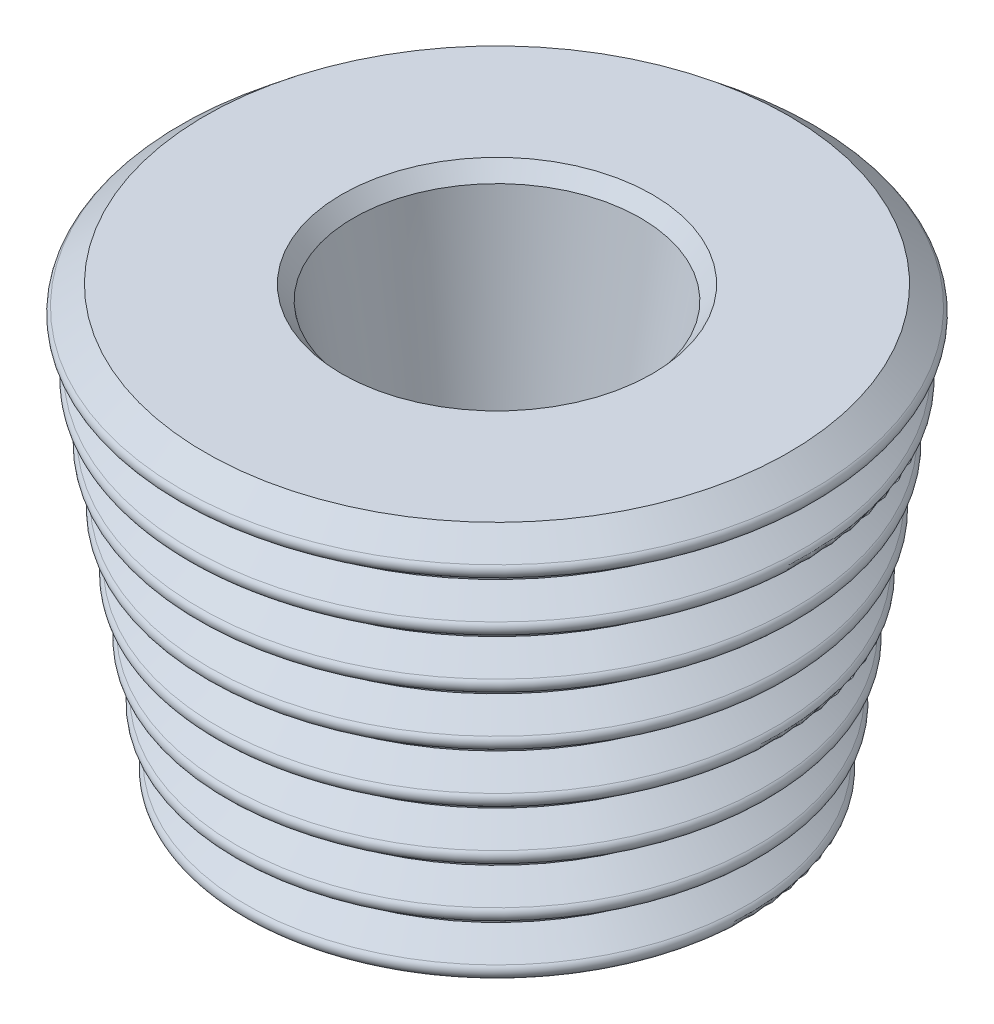
SolidWorks part; units mm, degrees
ref_plane "Plan de face" through (0, 0, 0) normal (0, 0, 1) x (1, 0, 0)
ref_plane "Plan de dessus" through (0, 0, 0) normal (0, 1, 0) x (1, 0, 0)
ref_plane "Plan de droite" through (0, 0, 0) normal (1, 0, 0) x (0, 0, -1)
sketch "Esquisse1" plane through (0, 0, 0) normal (0, 0, 1) x (1, 0, 0)
  line L0 (0, 0) -> (0, 20) construction
  line L1 (2.5, 0) -> (7.5, 0)
  line L2 (7.5, 0) -> (10, 15)
  line L3 (2.5, 0) -> (5, 15)
  line L4 (5, 15) -> (10, 15)
  line L5 (10, 15) -> (10.8238, 14.3219)
  line L6 (10.7526, 13.8947) -> (9.7534, 13.5204)
  line L7 (10.432, 11.9713) -> (9.4328, 11.5969)
  line L8 (9.6794, 13.0765) -> (10.5032, 12.3984)
  line L9 (10.1114, 10.0478) -> (9.1122, 9.6735)
  line L10 (9.3588, 11.1531) -> (10.1826, 10.4749)
  line L11 (9.7908, 8.1243) -> (8.7917, 7.75)
  line L12 (9.0383, 9.2296) -> (9.862, 8.5514)
  line L13 (9.4703, 6.2009) -> (8.4711, 5.8265)
  line L14 (8.7177, 7.3061) -> (9.5414, 6.628)
  line L15 (9.1497, 4.2774) -> (8.1505, 3.9031)
  line L16 (8.3971, 5.3827) -> (9.2209, 4.7045)
  line L17 (8.8291, 2.3539) -> (7.8299, 1.9796)
  line L18 (8.0765, 3.4592) -> (8.9003, 2.781)
  line L19 (8.5085, 0.4305) -> (7.5094, 0.0561)
  line L20 (7.756, 1.5357) -> (8.5797, 0.8576)
  arc A0 (9.4703, 6.2009) -> (9.5414, 6.628) centre (9.3826, 6.435) ccw
  arc A1 (9.1497, 4.2774) -> (9.2209, 4.7045) centre (9.062, 4.5115) ccw
  arc A2 (8.8291, 2.3539) -> (8.9003, 2.781) centre (8.7414, 2.588) ccw
  arc A3 (8.5085, 0.4305) -> (8.5797, 0.8576) centre (8.4208, 0.6646) ccw
  arc A4 (9.7908, 8.1243) -> (9.862, 8.5514) centre (9.7031, 8.3584) ccw
  arc A5 (10.1114, 10.0478) -> (10.1826, 10.4749) centre (10.0237, 10.2819) ccw
  arc A6 (10.432, 11.9713) -> (10.5032, 12.3984) centre (10.3443, 12.2054) ccw
  arc A7 (10.8238, 14.3219) -> (10.7526, 13.8947) centre (10.6649, 14.1288) cw
  point P46 (11.1581, 14.0466)
  dimension "D9" = 0.25
  dimension "D1" = 20
  dimension "D2" = 2.5
  dimension "D3" = 5
  dimension "D4" = 15
  dimension "D5" = 60
  dimension "D6" = 5
  dimension "D7" = 1.5
  dimension "D8" = 8
revolve "Révolution1" add sketch "Esquisse1" angle 360 about L0
chamfer "Chanfrein1" distance 0.5 angle 30 1 edges at (0, 15, -5)
chamfer "Chanfrein2" distance 0.25 angle 45 1 edges at (0, 0, -2.5)
ref_plane "Plan1" through (0, 14.5068, 0) normal (0, -1, 0) x (-1, 0, 0)
